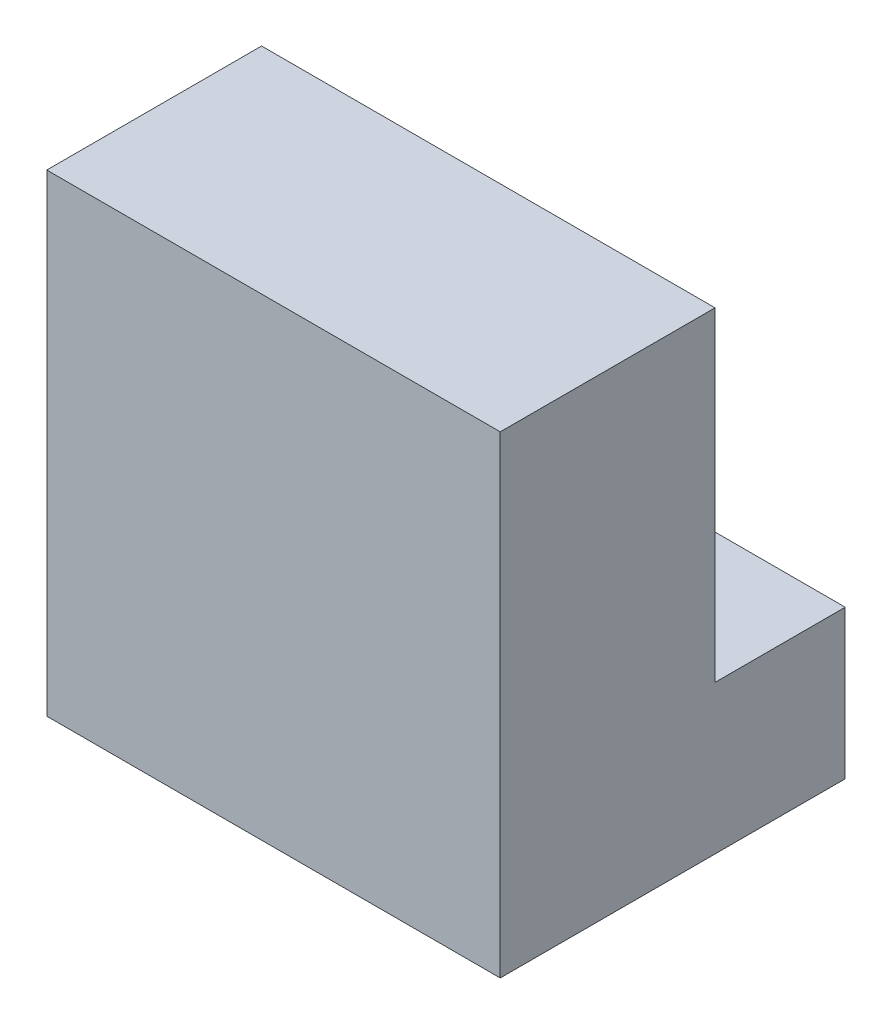
SolidWorks part; units mm, degrees
material "2024 Alloy"
ref_plane "X-Y Datum" through (0, 0, 0) normal (0, 0, 1) x (1, 0, 0)
ref_plane "X-Z Datum" through (0, 0, 0) normal (0, 1, 0) x (1, 0, 0)
ref_plane "Y-Z Datum" through (0, 0, 0) normal (1, 0, 0) x (0, 0, -1)
sketch "Sketch1" plane through (0, 0, 0) normal (0, 0, 1) x (1, 0, 0)
  line L1 (-20.9, 21.8) -> (20.9, 21.8)
  line L2 (-20.9, 21.8) -> (-20.9, -21.8)
  line L3 (-20.9, -21.8) -> (20.9, -21.8)
  line L4 (20.9, 21.8) -> (20.9, -21.8)
  line L5 (-20.9, 21.8) -> (20.9, -21.8) construction
  line L6 (-20.9, -21.8) -> (20.9, 21.8) construction
  point P0 (0, 0)
  dimension "D1" = 41.8
  dimension "D2" = 43.6
extrude "Boss-Extrude1" add sketch "Sketch1" along normal blind 19.8
sketch "Sketch2" plane through (0, 0, 0) normal (0, 0, -1) x (-1, 0, 0)
  line L0 (20.9, 21.8) -> (20.9, -21.8) construction
  line L1 (-20.9, -21.8) -> (20.9, -21.8)
  line L2 (-20.9, -21.8) -> (-20.9, -8.1)
  line L3 (-20.9, -8.1) -> (20.9, -8.1)
  line L4 (20.9, -21.8) -> (20.9, -8.1)
  dimension "D1" = 13.7
extrude "Boss-Extrude2" add sketch "Sketch2" along normal blind 12
